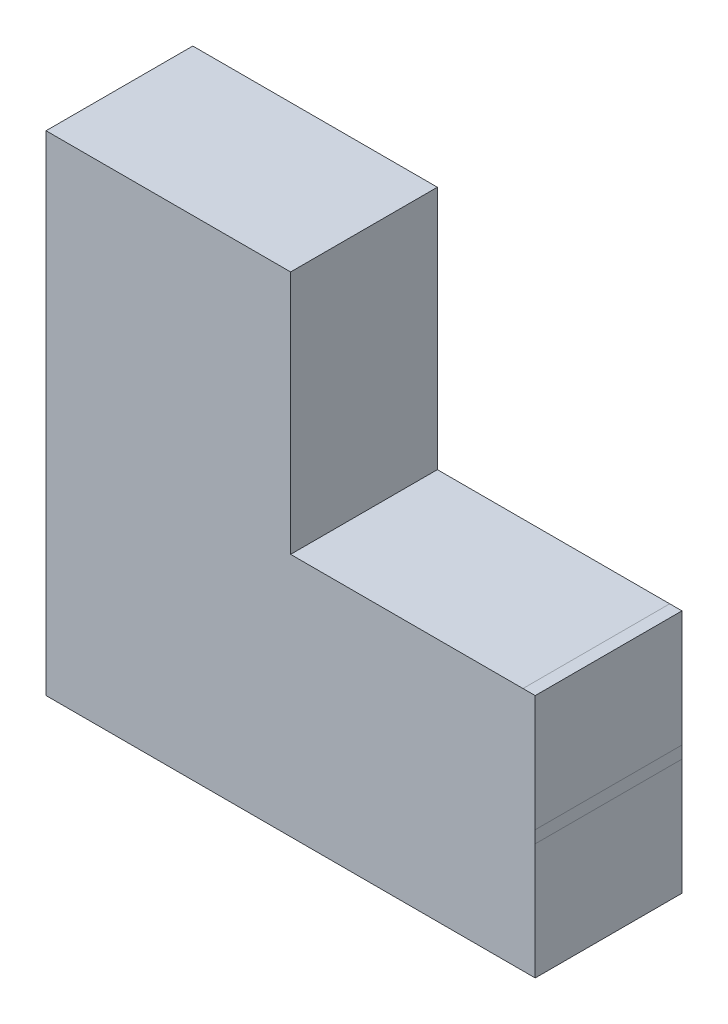
SolidWorks part; units mm, degrees
ref_plane "Front Plane" through (0, 0, 0) normal (0, 0, 1) x (1, 0, 0)
ref_plane "Top Plane" through (0, 0, 0) normal (0, 1, 0) x (1, 0, 0)
ref_plane "Right Plane" through (0, 0, 0) normal (1, 0, 0) x (0, 0, -1)
sketch "Sketch1" plane through (0, 0, 0) normal (0, 0, 1) x (1, 0, 0)
  line L0 (0, 0) -> (1000, 0)
  line L1 (1000, 0) -> (1000, 500)
  line L2 (1000, 500) -> (500, 500)
  line L3 (500, 500) -> (500, 1000)
  line L4 (500, 1000) -> (0, 1000)
  line L5 (0, 1000) -> (0, 0)
  dimension "D1" = 1000
  dimension "D2" = 500
  dimension "D3" = 500
  dimension "D4" = 1000
extrude "Boss-Extrude1" add sketch "Sketch1" along normal blind 300
sketch "Sketch3" plane through (1000, 0, 0) normal (1, 0, 0) x (0, 0, -1)
  line L1 (-300, 0) -> (-300, 500) construction
  line L2 (0, 0) -> (0, 500) construction
  line L4 (-300, 262.5) -> (0, 262.5)
  line L5 (-300, 237.5) -> (0, 237.5)
  line L6 (-300, 0) -> (0, 0) construction
  dimension "D2" = 25
  dimension "D3" = 237.5
split line "Split Line1"
sketch "Sketch4" plane through (0, 500, 0) normal (0, 1, 0) x (1, 0, 0)
  line L0 (975, 0) -> (975, -300)
  line L1 (1000, 0) -> (500, 0) construction
  line L2 (1000, -300) -> (500, -300) construction
  line L3 (1000, -300) -> (1000, 0) construction
  dimension "D1" = 25
split line "Split Line2"
equation "\"D3@Sketch3\"=(0.5-0.025)/2"
